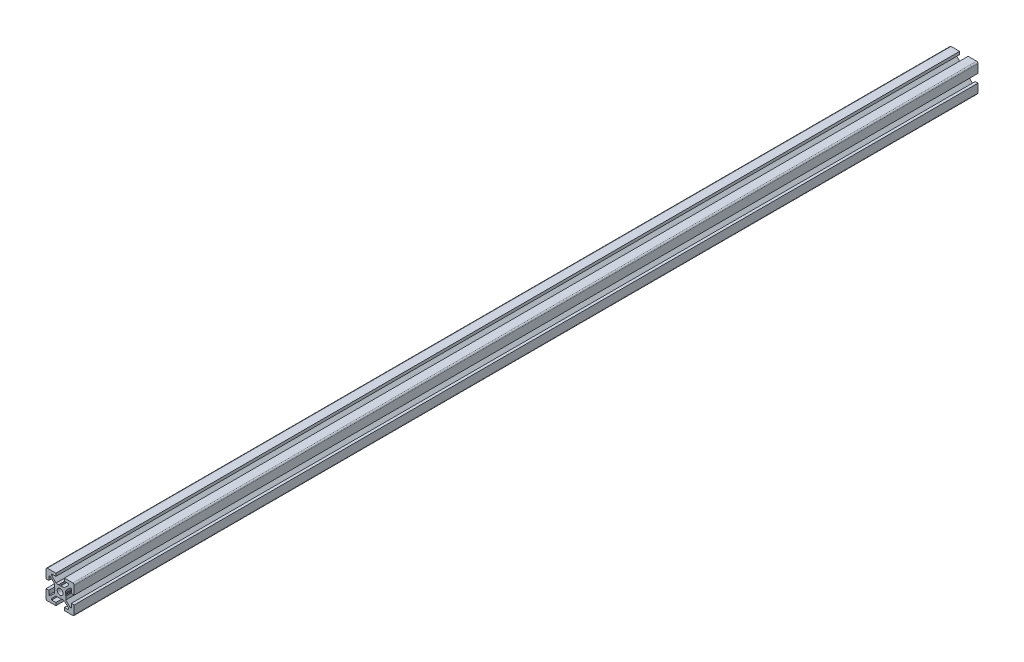
SolidWorks part; units mm, degrees
ref_plane "Front Plane" through (0, 0, 0) normal (0, 0, 1) x (1, 0, 0)
ref_plane "Top Plane" through (0, 0, 0) normal (0, 1, 0) x (1, 0, 0)
ref_plane "Right Plane" through (0, 0, 0) normal (1, 0, 0) x (0, 0, -1)
ref_plane "Plane1" through (0, 0, -2000) normal (0, 0, -1) x (-1, 0, 0)
sketch "Sketch1" plane through (0, 0, -2000) normal (0, 0, -1) x (-1, 0, 0)
  line L0 (10, -3) -> (8, -3)
  line L1 (8, -3) -> (8, -6)
  line L2 (8, -6) -> (7.0607, -6)
  line L3 (7.0607, -6) -> (4, -2.9393)
  line L4 (4, -2.9393) -> (4, -2.5)
  line L5 (4, -2.5) -> (3.751, -1.2189)
  line L6 (3.751, -1.2189) -> (3.933, -0.9036)
  line L7 (3.933, -0.4036) -> (3.7, 0)
  line L8 (3.7, 0) -> (3.933, 0.4036)
  line L9 (4, 0.6536) -> (4, 2.9393)
  line L10 (4, 2.9393) -> (7.0607, 6)
  line L11 (7.0607, 6) -> (8, 6)
  line L12 (8, 6) -> (8, 3)
  line L13 (8, 3) -> (10, 3)
  line L14 (10, 3) -> (10, 9)
  line L15 (9, 10) -> (3, 10)
  line L16 (3, 10) -> (3, 8)
  line L17 (3, 8) -> (6, 8)
  line L18 (6, 8) -> (6, 7.0607)
  line L19 (6, 7.0607) -> (2.9393, 4)
  line L20 (2.9393, 4) -> (2.5, 4)
  line L21 (2.5, 4) -> (1.2189, 3.751)
  line L22 (1.2189, 3.751) -> (0.9036, 3.933)
  line L23 (0.4036, 3.933) -> (0, 3.7)
  line L24 (0, 3.7) -> (-0.4036, 3.933)
  line L25 (-0.6536, 4) -> (-2.9393, 4)
  line L26 (-2.9393, 4) -> (-6, 7.0607)
  line L27 (-6, 7.0607) -> (-6, 8)
  line L28 (-6, 8) -> (-3, 8)
  line L29 (-3, 8) -> (-3, 10)
  line L30 (-3, 10) -> (-9, 10)
  line L31 (-10, 9) -> (-10, 3)
  line L32 (-10, 3) -> (-8, 3)
  line L33 (-8, 3) -> (-8, 6)
  line L34 (-8, 6) -> (-7.0607, 6)
  line L35 (-7.0607, 6) -> (-4, 2.9393)
  line L36 (-4, 2.9393) -> (-4, 2.5)
  line L37 (-4, 2.5) -> (-3.751, 1.2189)
  line L38 (-3.751, 1.2189) -> (-3.933, 0.9036)
  line L39 (-3.933, 0.4036) -> (-3.7, 0)
  line L40 (-3.7, 0) -> (-3.933, -0.4036)
  line L41 (-4, -0.6536) -> (-4, -2.9393)
  line L42 (-4, -2.9393) -> (-7.0607, -6)
  line L43 (-7.0607, -6) -> (-8, -6)
  line L44 (-8, -6) -> (-8, -3)
  line L45 (-8, -3) -> (-10, -3)
  line L46 (-10, -3) -> (-10, -9)
  line L47 (-9, -10) -> (-3, -10)
  line L48 (-3, -10) -> (-3, -8)
  line L49 (-3, -8) -> (-6, -8)
  line L50 (-6, -8) -> (-6, -7.0607)
  line L51 (-6, -7.0607) -> (-2.9393, -4)
  line L52 (-2.9393, -4) -> (-2.5, -4)
  line L53 (-2.5, -4) -> (-1.2189, -3.751)
  line L54 (-1.2189, -3.751) -> (-0.9036, -3.933)
  line L55 (-0.4036, -3.933) -> (0, -3.7)
  line L56 (0, -3.7) -> (0.4036, -3.933)
  line L57 (0.6536, -4) -> (2.9393, -4)
  line L58 (2.9393, -4) -> (6, -7.0607)
  line L59 (6, -7.0607) -> (6, -8)
  line L60 (6, -8) -> (3, -8)
  line L61 (3, -8) -> (3, -10)
  line L62 (3, -10) -> (9, -10)
  line L63 (10, -9) -> (10, -3)
  circle A0 centre (0, 0) radius 2.1
  arc A1 (3.933, -0.9036) -> (3.933, -0.4036) centre (3.5, -0.6536) ccw
  arc A2 (3.933, 0.4036) -> (4, 0.6536) centre (3.5, 0.6536) ccw
  arc A3 (10, 9) -> (9, 10) centre (9, 9) ccw
  arc A4 (0.9036, 3.933) -> (0.4036, 3.933) centre (0.6536, 3.5) ccw
  arc A5 (-0.4036, 3.933) -> (-0.6536, 4) centre (-0.6536, 3.5) ccw
  arc A6 (-9, 10) -> (-10, 9) centre (-9, 9) ccw
  arc A7 (-3.933, 0.9036) -> (-3.933, 0.4036) centre (-3.5, 0.6536) ccw
  arc A8 (-3.933, -0.4036) -> (-4, -0.6536) centre (-3.5, -0.6536) ccw
  arc A9 (-10, -9) -> (-9, -10) centre (-9, -9) ccw
  arc A10 (-0.9036, -3.933) -> (-0.4036, -3.933) centre (-0.6536, -3.5) ccw
  arc A11 (0.4036, -3.933) -> (0.6536, -4) centre (0.6536, -3.5) ccw
  arc A12 (9, -10) -> (10, -9) centre (9, -9) ccw
extrude "Boss-Extrude1" add sketch "Sketch1" against normal blind 640
